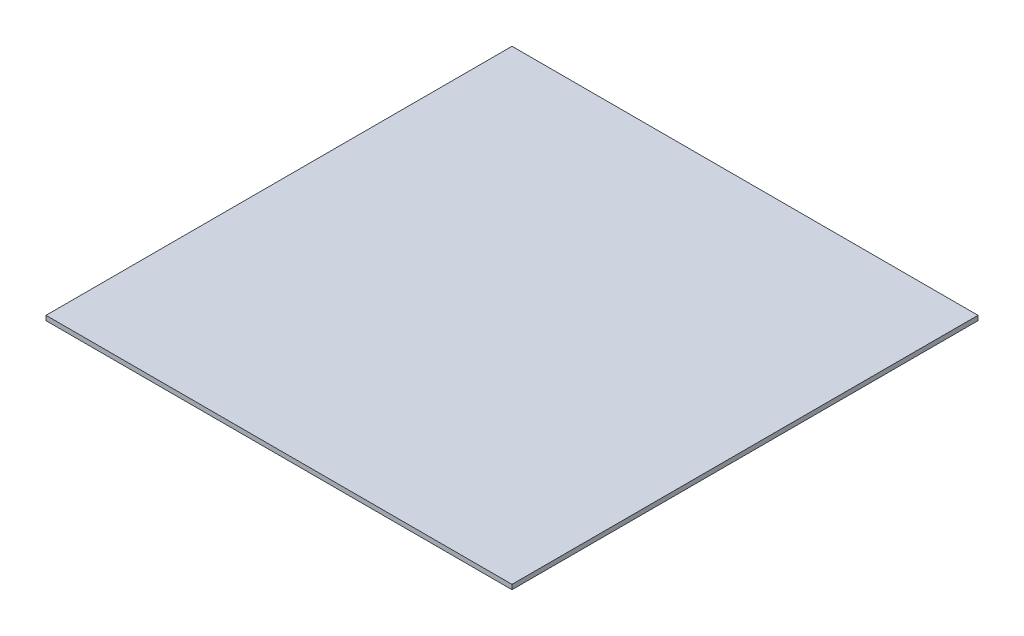
SolidWorks part; units mm, degrees
material "99.5% Aluminum Oxide"
ref_plane "Front Plane" through (0, 0, 0) normal (0, 0, 1) x (1, 0, 0)
ref_plane "Top Plane" through (0, 0, 0) normal (0, 1, 0) x (1, 0, 0)
ref_plane "Right Plane" through (0, 0, 0) normal (1, 0, 0) x (0, 0, -1)
sketch "Sketch1" plane through (0, 0, 0) normal (0, 1, 0) x (1, 0, 0)
  line L1 (-125, -125) -> (125, -125)
  line L2 (-125, -125) -> (-125, 125)
  line L3 (-125, 125) -> (125, 125)
  line L4 (125, -125) -> (125, 125)
  line L5 (-125, -125) -> (125, 125) construction
  line L6 (-125, 125) -> (125, -125) construction
  point P0 (0, 0)
  dimension "D1" = 250
extrude "Boss-Extrude1" add sketch "Sketch1" along normal mid plane 2.5
sketch "Sketch2" plane through (0, 1.25, 0) normal (0, 1, 0) x (1, 0, 0)
  line L0 (125, -125) -> (125, 125) construction
  line L1 (-123.5, -123.5) -> (123.5, -123.5)
  line L2 (-123.5, -123.5) -> (-123.5, 123.5)
  line L3 (-123.5, 123.5) -> (123.5, 123.5)
  line L4 (123.5, -123.5) -> (123.5, 123.5)
  line L5 (-123.5, -123.5) -> (123.5, 123.5) construction
  line L6 (-123.5, 123.5) -> (123.5, -123.5) construction
  point P0 (0, 0)
  dimension "D1" = 1.5
extrude "Cut-Extrude1" [suppressed] cut sketch "Sketch2" against normal blind 1
